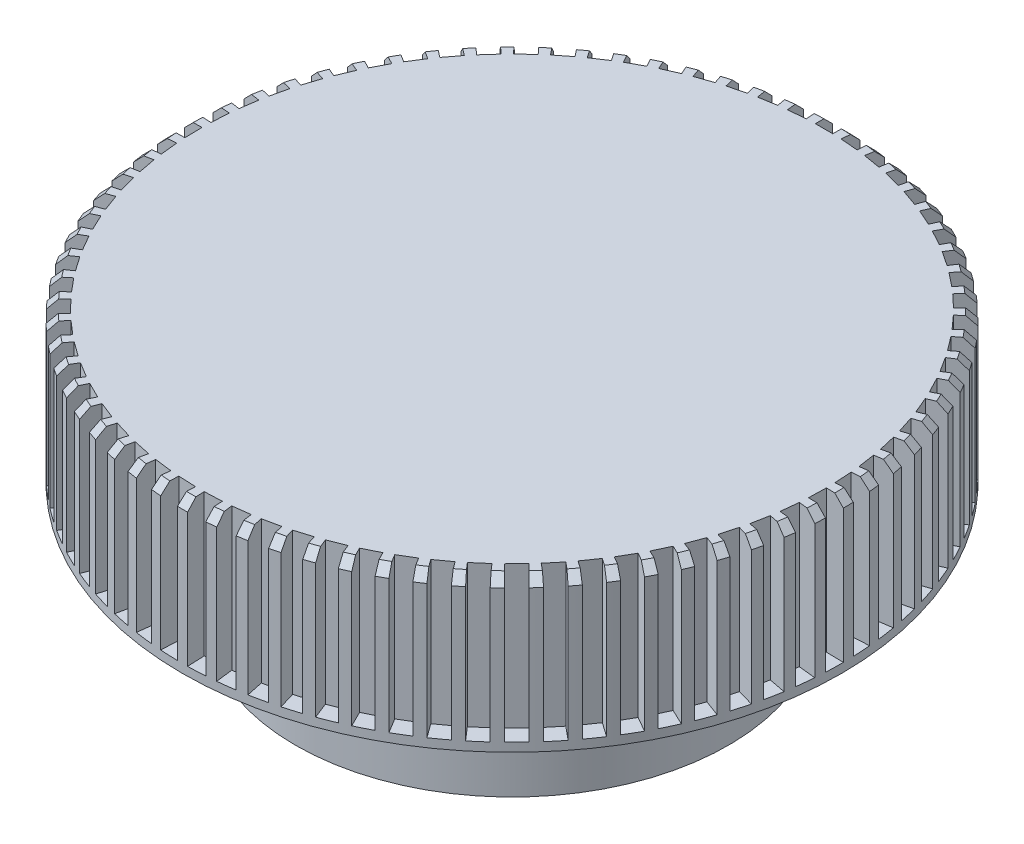
SolidWorks part; units mm, degrees
ref_plane "Front" through (0, 0, 0) normal (0, 0, 1) x (1, 0, 0)
ref_plane "Top" through (0, 0, 0) normal (0, 1, 0) x (1, 0, 0)
ref_plane "Right" through (0, 0, 0) normal (1, 0, 0) x (0, 0, -1)
ref_axis "Axis1" through (0, 50, 0) along (0, -1, 0)
sketch "Sketch1" plane through (0, 0, 0) normal (0, 0, 1) x (1, 0, 0)
  line L0 (0, 0) -> (9.5885, 0)
  line L1 (9.5885, 0) -> (9.5885, -4.3942)
  line L2 (9.5885, -4.3942) -> (7.4041, -4.3942)
  line L3 (7.4041, -4.3942) -> (7.4041, -1.1938)
  line L4 (7.4041, -1.1938) -> (6.2992, -1.1938)
  line L5 (6.2992, -1.1938) -> (6.2992, -7.8486)
  line L6 (6.2992, -7.8486) -> (4.7752, -7.8486)
  line L7 (4.7752, -7.8486) -> (4.7752, -1.1938)
  line L8 (4.7752, -1.1938) -> (2.7559, -1.1938)
  line L9 (2.7559, -1.1938) -> (2.7559, -4.6228)
  line L10 (2.7559, -4.6228) -> (0, -4.6228)
  line L11 (0, 0) -> (0, -4.6228)
  dimension "D1" = 2.7559
  dimension "OD" = 9.5885
  dimension "Top" = 1.1938
  dimension "Rim Height" = 4.3942
  dimension "ID" = 7.4041
  dimension "Post height" = 3.429
  dimension "Head OD" = 4.7752
  dimension "Inner height" = 6.6548
  dimension "Inner OD" = 6.2992
revolve "Revolve2" add sketch "Sketch1" angle 360 about axis through (0, 50, 0) along (0, -1, 0)
chamfer "Chamfer1" distance 0.254 angle 45 1 edges at (0, 0, 9.5885)
sketch "Sketch2" plane through (0, 0, 0) normal (0, 1, 0) x (1, 0, 0)
  line L0 (0, 0) -> (0, 9.5885) construction
  line L6 (0.254, 10.3505) -> (-0.254, 10.3505)
  line L7 (0.254, 10.3505) -> (0.254, 9.0805)
  line L8 (0.254, 9.0805) -> (-0.254, 9.0805)
  line L9 (-0.254, 10.3505) -> (-0.254, 9.0805)
  line L10 (0.254, 10.3505) -> (-0.254, 9.0805) construction
  line L11 (0.254, 9.0805) -> (-0.254, 10.3505) construction
  circle A1 centre (0, 0) radius 9.5885 construction
  point P5 (0, 9.7155)
  point P12 (0, 9.0805)
  dimension "D1" = 0.508
  dimension "D2" = 1.27
  dimension "D3" = 0.508
extrude "Cut-Extrude1" cut sketch "Sketch2" against normal offset from surface (4.1402 mm away) 0.254 up to face at (0, -4.3942, 9.5885)
pattern_circular "CirPattern1" count 75 over 360 about axis through (0, 0, 0) along (0, 1, 0) of "Cut-Extrude1"
sketch "Sketch3" [suppressed] plane through (0, 0, 0) normal (0, 1, 0) x (1, 0, 0)
  text T0 "<b>M6</b>" font "Century Gothic" height 3.175
extrude "Cut-Extrude2" [suppressed] cut sketch "Sketch3" against normal blind 0.508
sketch "Sketch4" [suppressed] plane through (0, 0, 0) normal (0, 1, 0) x (1, 0, 0)
  text T0 "<b>M8</b>" font "Century Gothic" height in points 16
extrude "Cut-Extrude3" [suppressed] cut sketch "Sketch4" against normal blind 0.508
sketch "Sketch5" [suppressed] plane through (0, 0, 0) normal (0, 1, 0) x (1, 0, 0)
  text T0 "<b>M5</b>" font "Century Gothic" height in points 14
extrude "Cut-Extrude4" [suppressed] cut sketch "Sketch5" against normal blind 0.508
sketch "Sketch6" [suppressed] plane through (0, 0, 0) normal (0, 1, 0) x (1, 0, 0)
  text T0 "<b>M4</b>"
extrude "Cut-Extrude5" [suppressed] cut sketch "Sketch6" against normal blind 0.508
sketch "Sketch7" [suppressed] plane through (0, 0, 0) normal (0, 1, 0) x (1, 0, 0)
  text T0 "<b>M3</b>"
extrude "Cut-Extrude6" [suppressed] cut sketch "Sketch7" against normal blind 0.508
sketch "Sketch8" [suppressed] plane through (0, 0, 0) normal (0, 1, 0) x (1, 0, 0)
  text T0 "<b>5/16</b>" font "Century Gothic" height in points 16
extrude "Cut-Extrude7" [suppressed] cut sketch "Sketch8" against normal blind 0.508
sketch "Sketch9" [suppressed] plane through (0, 0, 0) normal (0, 1, 0) x (1, 0, 0)
  text T0 "<b>4</b>"
extrude "Cut-Extrude8" [suppressed] cut sketch "Sketch9" against normal blind 0.508
sketch "Sketch10" [suppressed] plane through (0, 0, 0) normal (0, 1, 0) x (1, 0, 0)
  text T0 "<b>6</b>"
extrude "Cut-Extrude9" [suppressed] cut sketch "Sketch10" against normal blind 0.508
sketch "Sketch11" [suppressed] plane through (0, 0, 0) normal (0, 1, 0) x (1, 0, 0)
  text T0 "<b>8</b>" font "Century Gothic" height in points 14
extrude "Cut-Extrude10" [suppressed] cut sketch "Sketch11" against normal blind 0.508
sketch "Sketch12" [suppressed] plane through (0, 0, 0) normal (0, 1, 0) x (1, 0, 0)
  text T0 "<b>10</b>" font "Century Gothic" height in points 16
extrude "Cut-Extrude11" [suppressed] cut sketch "Sketch12" against normal blind 0.508
sketch "Sketch13" [suppressed] plane through (0, 0, 0) normal (0, 1, 0) x (1, 0, 0)
  text T0 "<b>1/4</b>" font "Century Gothic" height in points 16
extrude "Cut-Extrude12" [suppressed] cut sketch "Sketch13" against normal blind 0.508
